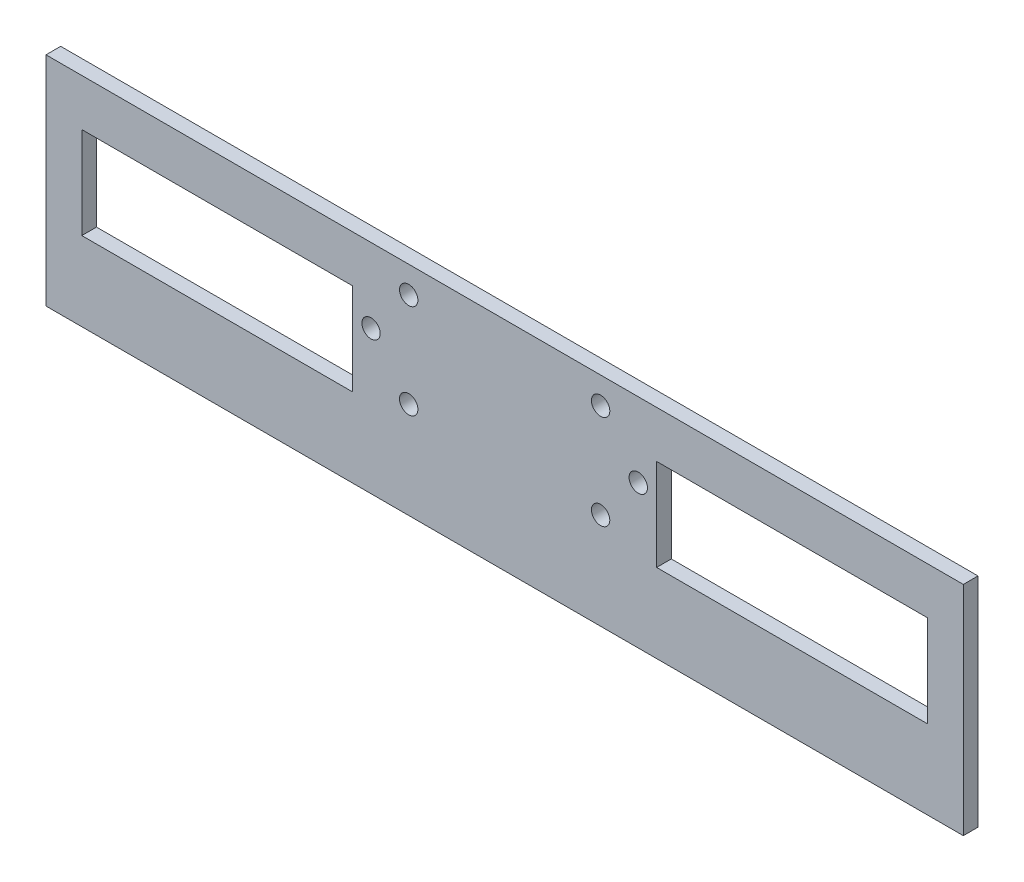
SolidWorks part; units mm, degrees
ref_plane "前视基准面" through (0, 0, 0) normal (0, 0, 1) x (1, 0, 0)
ref_plane "上视基准面" through (0, 0, 0) normal (0, 1, 0) x (1, 0, 0)
ref_plane "右视基准面" through (0, 0, 0) normal (1, 0, 0) x (0, 0, -1)
sketch "草图1" plane through (0, 0, 0) normal (0, 0, 1) x (1, 0, 0)
  line L0 (49.95, 0) -> (49.95, -37.3478) construction
  line L1 (0, 0) -> (99.9, 0)
  line L2 (0, 0) -> (0, -23.7)
  line L3 (0, -23.7) -> (99.9, -23.7)
  line L4 (99.9, 0) -> (99.9, -23.7)
  line L5 (3.9, -5.1) -> (33.4, -5.1)
  line L6 (3.9, -5.1) -> (3.9, -15.1)
  line L7 (3.9, -15.1) -> (33.4, -15.1)
  line L8 (33.4, -5.1) -> (33.4, -15.1)
  line L9 (96, -15.1) -> (66.5, -15.1)
  line L10 (66.5, -5.1) -> (66.5, -15.1)
  line L11 (96, -5.1) -> (66.5, -5.1)
  line L12 (96, -5.1) -> (96, -15.1)
  circle A0 centre (39.5, -2.9) radius 1
  circle A1 centre (35.4, -8.1) radius 1
  circle A2 centre (39.5, -13.2) radius 1
  circle A3 centre (60.4, -2.9) radius 1
  circle A4 centre (64.5, -8.1) radius 1
  circle A5 centre (60.4, -13.2) radius 1
  dimension "D7" = 2
  dimension "D8" = 2
  dimension "D9" = 2
  dimension "D1" = 99.9
  dimension "D2" = 23.7
  dimension "D3" = 3.9
  dimension "D4" = 5.1
  dimension "D5" = 10
  dimension "D6" = 29.5
  dimension "D10" = 2.9
  dimension "D11" = 5.2
  dimension "D12" = 5.1
  dimension "D13" = 4.1
  dimension "D14" = 2
extrude "凸台-拉伸1" add sketch "草图1" along normal blind 1.6
